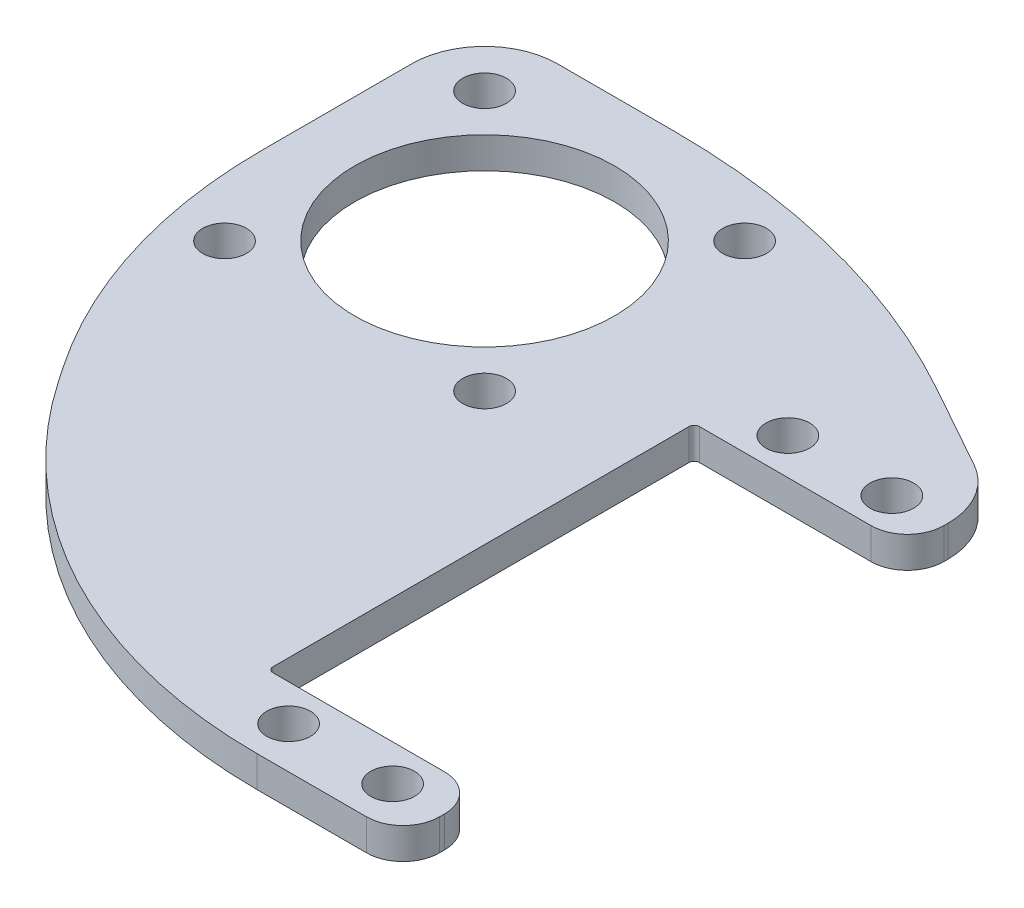
SolidWorks part; units mm, degrees
material "6061 Alloy"
ref_plane "Płaszczyzna przednia" through (0, 0, 0) normal (0, 0, 1) x (1, 0, 0)
ref_plane "Płaszczyzna górna" through (0, 0, 0) normal (0, 1, 0) x (1, 0, 0)
ref_plane "Płaszczyzna prawa" through (0, 0, 0) normal (1, 0, 0) x (0, 0, -1)
ref_plane "Płaszczyzna1"
sketch "Szkic1" plane through (0, 0, 0) normal (0, 1, 0) x (-1, 0, 0)
  line L0 (18.25, 18.25) -> (-5.7881, 53.6295)
  line L1 (-5.7881, 53.6295) -> (-35.7881, 53.6295)
  line L2 (-35.7881, 53.6295) -> (-45.7881, 53.6295)
  line L3 (-45.7881, 53.6295) -> (-45.7881, 46.1295)
  line L4 (-45.7881, 46.1295) -> (-25.2881, 46.1295)
  line L5 (-25.2881, 46.1295) -> (-25.2881, 5.1295)
  line L6 (-25.2881, 5.1295) -> (-45.7881, 5.1295)
  line L7 (-45.7881, 5.1295) -> (-45.7881, -2.8705)
  line L8 (-45.7881, -2.8705) -> (-18.25, -18.25)
  line L9 (-18.25, -18.25) -> (18.25, -18.25)
  line L10 (18.25, -18.25) -> (18.25, 18.25)
  circle A0 centre (0, 0) radius 12.5
  circle A1 centre (-12.5, -12.5) radius 2.1
  circle A2 centre (12.5, -12.5) radius 2.1
  circle A3 centre (-30.7881, 1.6295) radius 2.1
  circle A4 centre (12.5, 12.5) radius 2.1
  circle A5 centre (-40.7881, 49.6295) radius 2.1
  circle A6 centre (-30.7881, 49.6295) radius 2.1
  circle A7 centre (-12.5, 12.5) radius 2.1
  circle A8 centre (-40.7881, 1.6295) radius 2.1
  dimension "D1" = 25
  dimension "D4" = 4.2
  dimension "D5" = 4.2
  dimension "D6" = 4.2
  dimension "D7" = 4.2
  dimension "D9" = 4.2
  dimension "D10" = 4.2
  dimension "D11" = 4.2
  dimension "D12" = 4.2
  dimension "D2" = 25
  dimension "D3" = 25
  dimension "D8" = 48
  dimension "D13" = 41
  dimension "D14" = 10
  dimension "D15" = 30
  dimension "D16" = 36.5
  dimension "D17" = 36.5
  dimension "D18" = 8
extrude "Wyciągnięcie proste1" add sketch "Szkic1" along normal blind 3 contours L9 L10 L0 L1 L2 L3 L4 L5 L6 L7 L8 A8 A7 A6 A5 A4 A3 A2 A1 A0
fillet "Zaokrąglenie1" radius 0.5 2 edges at (25.2881, 1.5, 46.1295) (25.2881, 1.5, 5.1295)
fillet "Zaokrąglenie3" radius 3.5 3 edges at (45.7881, 1.5, 53.6295) (45.7881, 1.5, 46.1295) (45.7881, 1.5, 5.1295)
fillet "Zaokrąglenie4" radius 7 1 edges at (45.7881, 1.5, -2.8705)
fillet "Zaokrąglenie5" radius 70 1 edges at (18.25, 1.5, -18.25)
fillet "Zaokrąglenie6" radius 49 1 edges at (5.7881, 1.5, 53.6295)
fillet "Zaokrąglenie7" radius 49 1 edges at (-18.25, 1.5, 18.25)
fillet "Zaokrąglenie8" radius 7 1 edges at (-18.25, 1.5, -18.25)
